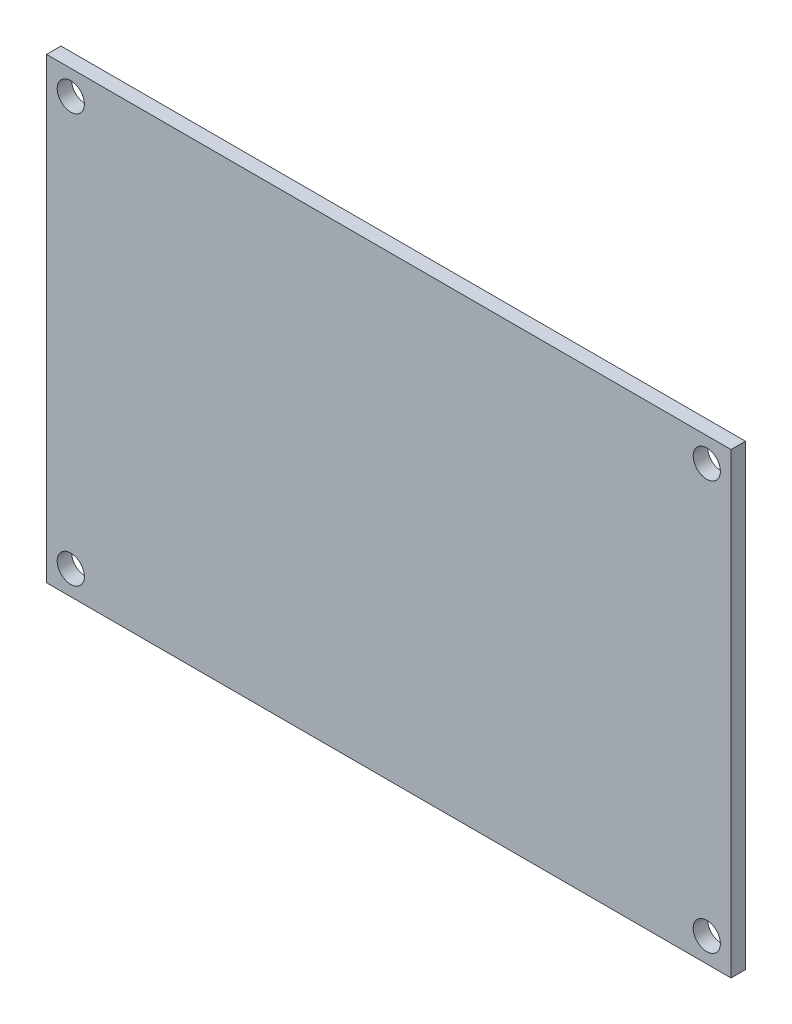
SolidWorks part; units mm, degrees
ref_plane "Front Plane" through (0, 0, 0) normal (0, 0, 1) x (1, 0, 0)
ref_plane "Top Plane" through (0, 0, 0) normal (0, 1, 0) x (1, 0, 0)
ref_plane "Right Plane" through (0, 0, 0) normal (1, 0, 0) x (0, 0, -1)
sketch "Sketch1" plane through (0, 0, 0) normal (0, 0, 1) x (1, 0, 0)
  line L0 (2.1336, 38.0746) -> (58.0136, 38.0746) construction
  line L1 (0, 0) -> (60.1472, 0)
  line L2 (0, 0) -> (0, 40.2082)
  line L3 (0, 40.2082) -> (60.1472, 40.2082)
  line L4 (60.1472, 0) -> (60.1472, 40.2082)
  line L5 (58.0136, 38.0746) -> (58.0136, 2.1336) construction
  line L6 (58.0136, 2.1336) -> (2.1336, 2.1336) construction
  line L7 (2.1336, 2.1336) -> (2.1336, 38.0746) construction
  line L8 (2.1336, 20.1041) -> (0, 20.1041) construction
  line L9 (30.0736, 40.2082) -> (30.0736, 38.0746) construction
  circle A0 centre (2.1336, 38.0746) radius 1.1938
  circle A1 centre (58.0136, 38.0746) radius 1.1938
  circle A2 centre (2.1336, 2.1336) radius 1.1938
  circle A3 centre (58.0136, 2.1336) radius 1.1938
  dimension "D3" = 2.3876
  dimension "D1" = 40.2082
  dimension "D2" = 60.1472
  dimension "D4" = 35.941
  dimension "D5" = 55.88
extrude "Boss-Extrude1" add sketch "Sketch1" along normal blind 1.27
